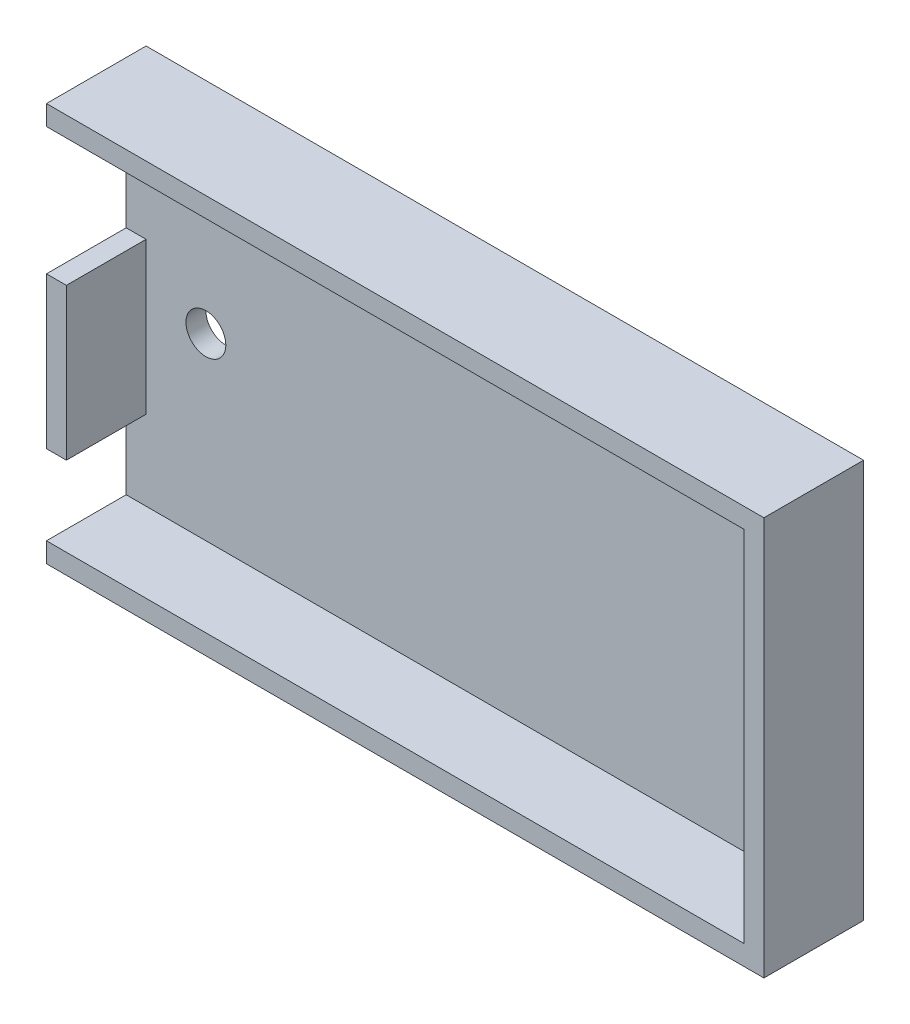
SolidWorks part; units mm, degrees
material "ABS"
ref_plane "Front Plane" through (0, 0, 0) normal (0, 0, 1) x (1, 0, 0)
ref_plane "Top Plane" through (0, 0, 0) normal (0, 1, 0) x (1, 0, 0)
ref_plane "Right Plane" through (0, 0, 0) normal (1, 0, 0) x (0, 0, -1)
sketch "Sketch1" plane through (0, 0, 0) normal (0, 0, 1) x (1, 0, 0)
  line L1 (-57.15, -31.75) -> (57.15, -31.75)
  line L2 (-57.15, -31.75) -> (-57.15, 31.75)
  line L3 (-57.15, 31.75) -> (57.15, 31.75)
  line L4 (57.15, -31.75) -> (57.15, 31.75)
  line L5 (0, 31.75) -> (0, -31.75) construction
  line L6 (-57.15, 0) -> (57.15, 0) construction
  point P0 (0, 0)
  dimension "D1" = 63.5
  dimension "D2" = 114.3
extrude "Boss-Extrude1" add sketch "Sketch1" along normal blind 3.175
sketch "Sketch2" plane through (0, 0, 3.175) normal (0, 0, 1) x (1, 0, 0)
  line L4 (-57.15, -31.75) -> (57.15, -31.75) construction
  line L5 (57.15, -31.75) -> (57.15, 31.75) construction
  line L6 (-57.15, 31.75) -> (-57.15, -31.75) construction
  line L7 (57.15, 31.75) -> (-57.15, 31.75) construction
  line L8 (53.975, -28.575) -> (53.975, 28.575)
  line L9 (53.975, 28.575) -> (-53.975, 28.575)
  line L10 (-53.975, 28.575) -> (-53.975, -28.575)
  line L11 (-53.975, -28.575) -> (53.975, -28.575)
  line L12 (53.975, -28.575) -> (53.975, 28.575)
  line L13 (53.975, 28.575) -> (-53.975, 28.575)
  line L14 (-53.975, 28.575) -> (-53.975, -28.575)
  line L15 (-53.975, -28.575) -> (53.975, -28.575)
  line L16 (-57.15, -31.75) -> (57.15, -31.75)
  line L17 (57.15, -31.75) -> (57.15, 31.75)
  line L18 (-57.15, 31.75) -> (-57.15, -31.75)
  line L19 (57.15, 31.75) -> (-57.15, 31.75)
  dimension "D1" = 3.175
extrude "Boss-Extrude2" add sketch "Sketch2" along normal blind 12.7
sketch "Sketch3" plane through (-57.15, 0, 0) normal (-1, 0, 0) x (0, 0, 1)
  line L0 (0, 31.75) -> (0, -31.75) construction
  line L1 (15.875, -28.575) -> (3.175, -28.575)
  line L2 (15.875, -28.575) -> (15.875, -15.875)
  line L3 (15.875, -15.875) -> (3.175, -15.875)
  line L4 (3.175, -28.575) -> (3.175, -15.875)
  line L6 (15.875, 31.75) -> (15.875, -31.75) construction
  line L7 (15.875, -31.75) -> (0, -31.75) construction
  line L9 (15.875, 28.575) -> (3.175, 28.575)
  line L10 (15.875, 28.575) -> (15.875, 8.255)
  line L11 (15.875, 8.255) -> (3.175, 8.255)
  line L12 (3.175, 28.575) -> (3.175, 8.255)
  line L13 (15.875, 31.75) -> (0, 31.75) construction
  dimension "D1" = 3.175
  dimension "D2" = 12.7
  dimension "D3" = 3.175
  dimension "D4" = 20.32
  dimension "D5" = 3.175
  dimension "D6" = 3.175
extrude "Cut-Extrude1" cut sketch "Sketch3" against normal up to next
sketch "Sketch4" plane through (0, 0, 3.175) normal (0, 0, 1) x (1, 0, 0)
  line L0 (-57.15, 8.255) -> (-57.15, -15.875) construction
  line L1 (-69.4254, 0) -> (82.7687, 0) construction
  circle A0 centre (-44.45, 0) radius 3.175
  circle A1 centre (44.45, 0) radius 3.175
  dimension "D1" = 6.35
  dimension "D2" = 88.9
  dimension "D3" = 12.7
extrude "Cut-Extrude2" cut sketch "Sketch4" against normal up to next
